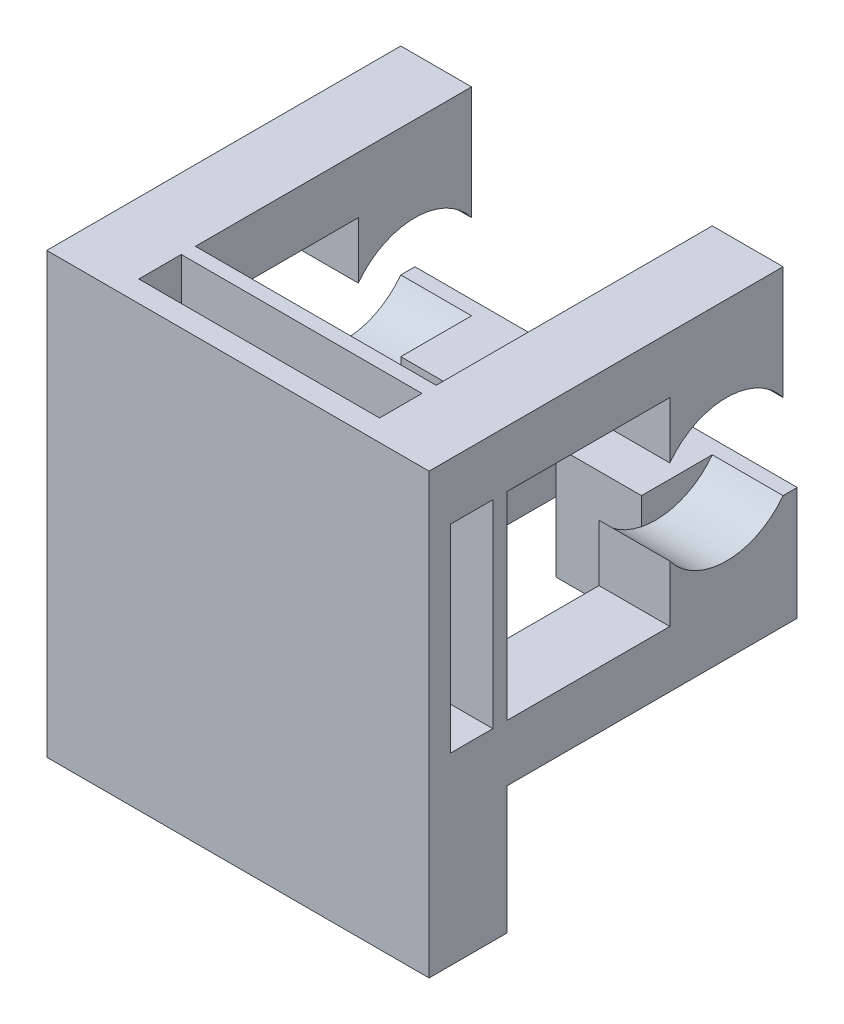
SolidWorks part; units mm, degrees
ref_plane "Front Plane" through (0, 0, 0) normal (0, 0, 1) x (1, 0, 0)
ref_plane "Top Plane" through (0, 0, 0) normal (0, 1, 0) x (1, 0, 0)
ref_plane "Right Plane" through (0, 0, 0) normal (1, 0, 0) x (0, 0, -1)
sketch "Sketch1" plane through (0, 0, 0) normal (0, 0, 1) x (1, 0, 0)
  line L1 (0, 0) -> (68.58, 0)
  line L2 (0, 0) -> (0, 55.88)
  line L3 (0, 55.88) -> (68.58, 55.88)
  line L4 (68.58, 0) -> (68.58, 55.88)
  dimension "D1" = 55.88
  dimension "D2" = 68.58
extrude "Boss-Extrude1" add sketch "Sketch1" along normal blind 3.81 contours L1 L4 L3 L2
sketch "Sketch2" plane through (0, 0, 0) normal (0, 0, -1) x (-1, 0, 0)
  line L0 (-12.7, 55.88) -> (-12.7, 45.72)
  line L1 (-68.58, 55.88) -> (-55.88, 55.88)
  line L2 (-68.58, 55.88) -> (-68.58, 45.72)
  line L3 (-68.58, 45.72) -> (-55.88, 45.72)
  line L4 (-55.88, 55.88) -> (-55.88, 45.72)
  line L5 (-12.7, 55.88) -> (0, 55.88)
  line L6 (0, 55.88) -> (0, 45.72)
  line L7 (-12.7, 45.72) -> (0, 45.72)
  line L8 (-12.7, 10.16) -> (-12.7, 0)
  line L9 (-12.7, 10.16) -> (0, 10.16)
  line L10 (0, 10.16) -> (0, 0)
  line L11 (-12.7, 0) -> (0, 0)
  line L12 (-68.58, 10.16) -> (-68.58, 0)
  line L13 (-68.58, 10.16) -> (-55.88, 10.16)
  line L14 (-55.88, 10.16) -> (-55.88, 0)
  line L15 (-68.58, 0) -> (-55.88, 0)
  line M5 (-68.58, 0) -> (0, 0)
  line M6 (0, 0) -> (0, 55.88)
  line M7 (0, 55.88) -> (-68.58, 55.88)
  line M8 (-68.58, 55.88) -> (-68.58, 0)
  dimension "D1" = 12.7
  dimension "D2" = 10.16
  dimension "D3" = 2
  dimension "D4" = 2
extrude "Boss-Extrude2" add sketch "Sketch2" along normal blind 59.69 contours L4 L3 M7 M8 | L0 L7 M6 M7 | L9 L8 M5 M6 | L14 L13 M8 M5
sketch "Sketch4" plane through (68.58, 0, 0) normal (1, 0, 0) x (0, 0, -1)
  line L0 (59.69, 55.88) -> (59.69, 45.72) construction
  circle A0 centre (49.53, 27.94) radius 12.7
  dimension "D1" = 25.4
  dimension "D2" = 10.16
sketch "Sketch6" plane through (0, 10.16, 0) normal (0, 1, 0) x (1, 0, 0)
  line L0 (68.58, 59.69) -> (68.58, 0) construction
  line L1 (55.88, 59.69) -> (68.58, 59.69)
  line L2 (55.88, 59.69) -> (55.88, 39.37)
  line L3 (55.88, 39.37) -> (68.58, 39.37)
  line L4 (68.58, 59.69) -> (68.58, 39.37)
  line L5 (0, 59.69) -> (0, 39.37)
  line L6 (0, 59.69) -> (12.7, 59.69)
  line L7 (12.7, 59.69) -> (12.7, 39.37)
  line L8 (0, 39.37) -> (12.7, 39.37)
  dimension "D1" = 20.32
  dimension "D2" = 2
extrude "Boss-Extrude3" add sketch "Sketch6" along normal blind 35.56
extrude "Cut-Extrude1" cut sketch "Sketch4" against normal through all contours A0
ref_plane "Plane1" through (0, 0, -7.62) normal (0, 0, -1) x (-1, 0, 0)
sketch "Sketch7" plane through (0, 0, -7.62) normal (0, 0, -1) x (-1, 0, 0)
  line L1 (-68.58, 55.88) -> (0, 55.88)
  line L2 (-68.58, 55.88) -> (-68.58, 0)
  line L3 (-68.58, 0) -> (0, 0)
  line L4 (0, 55.88) -> (0, 0)
  line L5 (-55.88, 0) -> (-12.7, 0)
  line L6 (-55.88, 0) -> (-55.88, -22.86)
  line L7 (-55.88, -22.86) -> (-12.7, -22.86)
  line L8 (-12.7, 0) -> (-12.7, -22.86)
  dimension "D1" = 43.18
  dimension "D2" = 22.86
extrude "Boss-Extrude4" add sketch "Sketch7" along normal blind 2.54 contours L4 L1 L2 L3 | L8 L3 L6 L7
sketch "Sketch8" plane through (0, 0, -10.16) normal (0, 0, -1) x (-1, 0, 0)
  line L2 (-12.7, 0) -> (0, 0) construction
  line L3 (-68.58, 45.72) -> (-68.58, 10.16) construction
  circle A0 centre (-34.29, -10.16) radius 3.429
  circle A1 centre (-34.29, 27.94) radius 7.493
  point P4 (-34.5528, 27.94)
  point P5 (-34.29, 27.94)
  point P6 (-34.29, 4.941)
  point P11 (-23.601, 9.9351)
  dimension "D2" = 27.94
  dimension "D3" = 38.1
  dimension "D1" = 34.29
  dimension "D4" = 14.986
  dimension "D5" = 6.858
extrude "Cut-Extrude2" cut sketch "Sketch8" against normal blind 2.54 contours A0 | A1
sketch "Sketch9" plane through (0, 0, -59.69) normal (0, 0, -1) x (-1, 0, 0)
  line L1 (-68.58, 20.32) -> (0, 20.32)
  line L2 (-68.58, 20.32) -> (-68.58, 0)
  line L3 (-68.58, 0) -> (0, 0)
  line L4 (0, 20.32) -> (0, 0)
extrude "Boss-Extrude5" add sketch "Sketch9" along normal blind 2.54
ref_plane "Plane2" through (34.29, 0, 0) normal (-1, 0, 0) x (0, 0, 1)
sketch "Sketch10" plane through (0, 0, 0) normal (0, -1, 0) x (1, 0, 0)
  line L0 (55.88, -59.69) -> (12.7, -59.69) construction
  line L1 (28.067, -58.166) -> (40.513, -58.166)
  line L2 (28.067, -58.166) -> (28.067, -61.214)
  line L3 (28.067, -61.214) -> (40.513, -61.214)
  line L4 (40.513, -58.166) -> (40.513, -61.214)
  line L5 (28.067, -58.166) -> (40.513, -61.214) construction
  line L6 (28.067, -61.214) -> (40.513, -58.166) construction
  point P0 (34.29, -59.69)
  dimension "D1" = 1.524
  dimension "D2" = 12.446
extrude "Cut-Extrude3" cut sketch "Sketch10" against normal up to next
sketch "Sketch11" plane through (0, 0, -59.69) normal (0, 0, 1) x (1, 0, 0)
  line L1 (12.7, 20.32) -> (28.067, 20.32)
  line L2 (12.7, 20.32) -> (12.7, 0)
  line L3 (12.7, 0) -> (28.067, 0)
  line L4 (28.067, 20.32) -> (28.067, 0)
  line L5 (40.513, 20.32) -> (55.88, 20.32)
  line L6 (40.513, 20.32) -> (40.513, 0)
  line L7 (40.513, 0) -> (55.88, 0)
  line L8 (55.88, 20.32) -> (55.88, 0)
extrude "Boss-Extrude6" add sketch "Sketch11" along normal blind 12.7
sketch "Sketch12" plane through (0, 0, 0) normal (0, -1, 0) x (1, 0, 0)
  line L0 (12.7, -10.16) -> (0, -10.16)
  line L1 (0, 3.81) -> (0, -62.23) construction
  line L2 (0, -10.16) -> (0, 3.81)
  line L3 (0, 3.81) -> (68.58, 3.81)
  line L4 (68.58, 3.81) -> (68.58, -10.16)
  line L5 (68.58, 3.81) -> (68.58, -62.23) construction
  line L6 (68.58, -10.16) -> (55.88, -10.16)
  line L7 (55.88, -10.16) -> (55.88, 0)
  line L8 (55.88, 0) -> (12.7, 0)
  line L9 (12.7, 0) -> (12.7, -10.16)
  point P5 (55.88, -10.16)
extrude "Boss-Extrude7" add sketch "Sketch12" along normal up to surface (22.86 mm away) up to face at (34.29, -22.86, -8.89)
